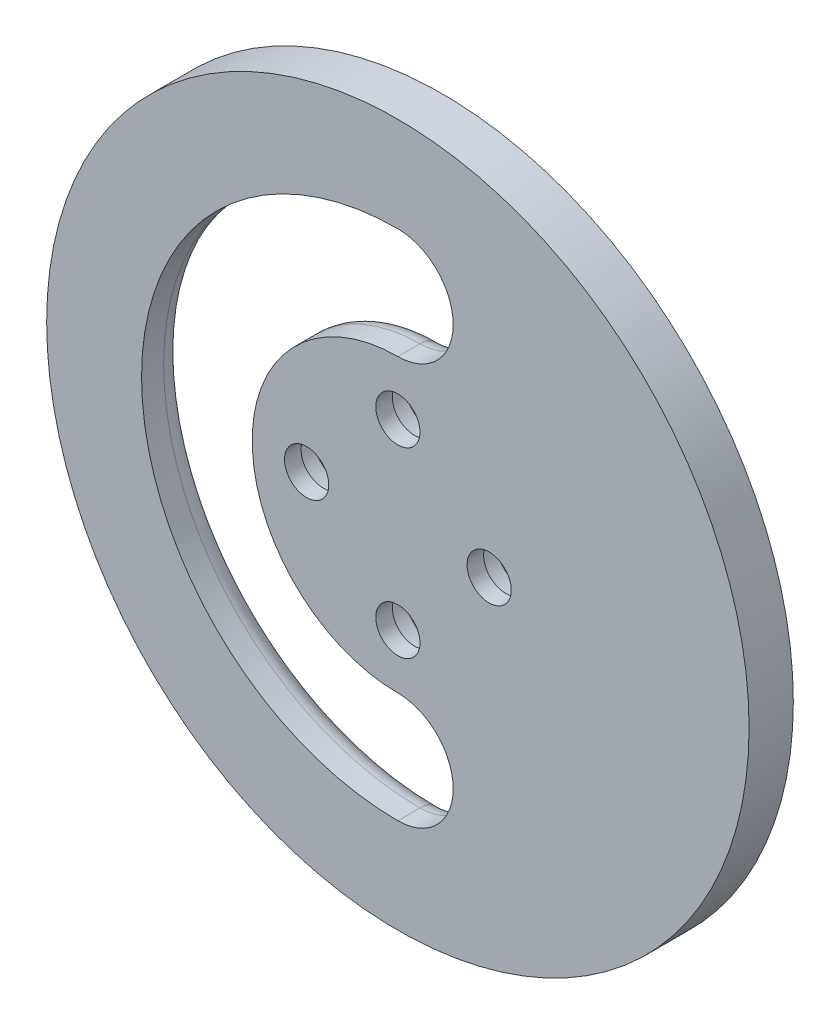
SolidWorks part; units mm, degrees
material "Nylon PA 12"
ref_plane "Front Plane" through (0, 0, 0) normal (0, 0, 1) x (1, 0, 0)
ref_plane "Top Plane" through (0, 0, 0) normal (0, 1, 0) x (1, 0, 0)
ref_plane "Right Plane" through (0, 0, 0) normal (1, 0, 0) x (0, 0, -1)
sketch "Sketch1" plane through (0, 0, 0) normal (0, 0, 1) x (1, 0, 0)
  line L0 (0, 8.25) -> (0, -8.25) construction
  line L1 (-8.25, 0) -> (8.25, 0) construction
  circle A0 centre (0, 8.25) radius 1.33 construction
  circle A1 centre (8.25, 0) radius 1.33 construction
  circle A2 centre (0, -8.25) radius 1.33 construction
  circle A3 centre (-8.25, 0) radius 1.33 construction
  circle A5 centre (0, 0) radius 31.75
  point P5 (0, 0)
  point P6 (0, 0)
  dimension "D1" = 4
extrude "Elbow Plate" add sketch "Sketch1" along normal blind 4
sketch "Sketch3" plane through (0, 0, 0) normal (0, 0, -1) x (-1, 0, 0)
  line L0 (8.25, 0) -> (-8.25, 0) construction
  circle A0 centre (0, 0) radius 26.75 construction
  circle A1 centre (0, 0) radius 31.75 construction
  circle A9 centre (0, 26.75) radius 1.33
  circle A10 centre (23.1662, 13.375) radius 1.33
  circle A11 centre (23.1662, -13.375) radius 1.33
  circle A12 centre (0, -26.75) radius 1.33
  circle A13 centre (-23.1662, -13.375) radius 1.33
  circle A14 centre (-23.1662, 13.375) radius 1.33
  dimension "D1" = 5
  dimension "D2" = 6
  dimension "D3" = 53.5
  dimension "D4" = 2.66
extrude "Screw Holes" cut sketch "Sketch3" against normal blind 3
sketch "Sketch4" plane through (0, 0, 4) normal (0, 0, 1) x (1, 0, 0)
  line L0 (0, 0) -> (15.3714, -15.3714) construction
  line L1 (-8.25, 0) -> (8.25, 0) construction
  line L2 (0, 0) -> (16.7612, 16.7612) construction
  line L3 (0, -8.25) -> (0, -33.1782) construction
  line L4 (0, 8.25) -> (0, 26.75) construction
  circle A0 centre (0, -26.75) radius 1.33 construction
  arc A1 (0, -23.1723) -> (0, -13.17) centre (0, -18.1712) ccw
  arc A2 (0, 13.17) -> (0, 23.1723) centre (0, 18.1712) ccw
  arc A3 (0, 18.1712) -> (4.9536, -17.4829) centre (0, 0) ccw construction
  arc A4 (0, 13.17) -> (0, -13.17) centre (0, 0) ccw
  arc A5 (0, 23.1723) -> (0, -23.1723) centre (0, 0) ccw
  dimension "D4" = 13.17
  dimension "D5" = 23.1723
  dimension "D1" = 270
  dimension "D2" = 45
  dimension "D3" = 18.5
extrude "Cable Slot" cut sketch "Sketch4" against normal blind 4
fillet "Fillet1" radius 2 4 edges at (5.0012, 18.1712, 0) (-13.17, 0, 0) (5.0012, -18.1712, 0) (-23.1723, 0, 0)
sketch "Sketch2" plane through (0, 0, 0) normal (0, 0, -1) x (-1, 0, 0)
  line L0 (8.25, 0) -> (-8.25, 0) construction
  circle A0 centre (0, 0) radius 8.25 construction
  circle A1 centre (0, 8.25) radius 1.33
  circle A2 centre (8.25, 0) radius 1.33
  circle A3 centre (0, -8.25) radius 1.33
  circle A4 centre (-8.25, 0) radius 1.33
  point P14 (-8.25, 0)
  point P15 (0, 8.25)
  point P16 (8.25, 0)
  point P17 (0, -8.25)
  point P18 (0, 8.25)
  point P19 (8.25, 0)
  dimension "D2" = 2.66
  dimension "D3" = 16.5
  dimension "D1" = 4
hole_wizard "CBORE for M6 Hex Head Bolt1" positions "Sketch15" profile "Sketch16" counterbore size "M6" standard "ANSI Metric" end condition through all
sketch "Sketch15" plane through (0, 0, 0) normal (0, 0, -1) x (-1, 0, 0)
  point P0 (-8.25, 0)
  point P3 (0, -8.25)
  point P6 (8.25, 0)
  point P9 (0, 8.25)
sketch "Sketch16" plane through (8.25, 0, 0) normal (1, 0, 0) x (0, 1, 0)
  line L0 (0, 0) -> (0, 4)
  line L1 (0, 4) -> (2, 4)
  line L3 (2, 4) -> (2, 2.5)
  line L4 (2, 2.5) -> (3.75, 2.5)
  line L5 (3.75, 2.5) -> (3.75, 0)
  line L7 (3.75, 0) -> (0, 0)
  line L11 (0, -6.35) -> (0, 107.95) construction
  dimension "Thru Hole Dia." = 4
  dimension "Thru Hole Depth" = 4
  dimension "C'Bore Dia." = 7.5
  dimension "C'Bore Depth" = 2.5
